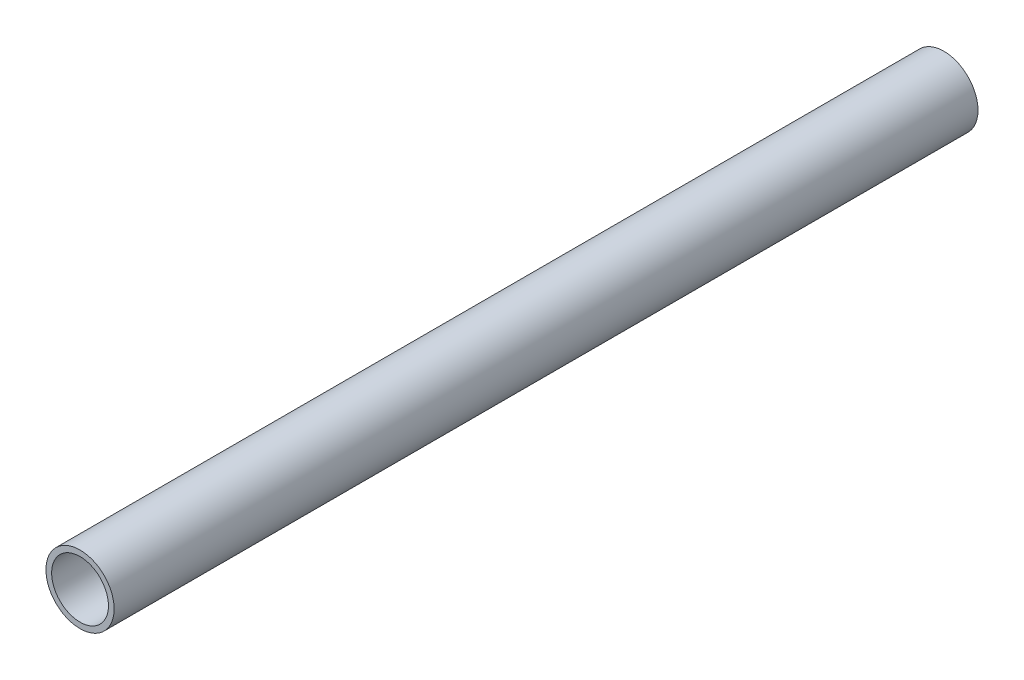
SolidWorks part; units mm, degrees
ref_plane "前视基准面" through (0, 0, 0) normal (0, 0, 1) x (1, 0, 0)
ref_plane "上视基准面" through (0, 0, 0) normal (0, 1, 0) x (1, 0, 0)
ref_plane "右视基准面" through (0, 0, 0) normal (1, 0, 0) x (0, 0, -1)
other "Configuration Table"
sketch "Sketch1" plane through (0, 0, 0) normal (0, 0, 1) x (1, 0, 0)
  circle A0 centre (0, 0) radius 1.5
  circle A1 centre (0, 0) radius 1.25
extrude "body tube" add sketch "Sketch1" along normal blind 37.9984
